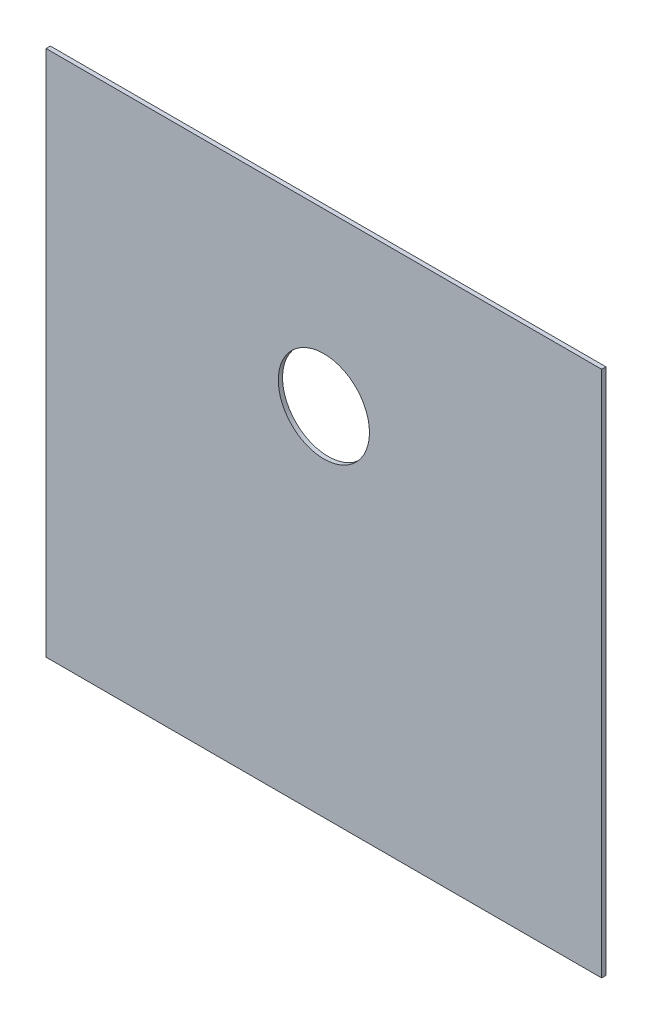
SolidWorks part; units mm, degrees
ref_plane "Front Plane" through (0, 0, 0) normal (0, 0, 1) x (1, 0, 0)
ref_plane "Top Plane" through (0, 0, 0) normal (0, 1, 0) x (1, 0, 0)
ref_plane "Right Plane" through (0, 0, 0) normal (1, 0, 0) x (0, 0, -1)
sketch "Sketch1" plane through (0, 0, 0) normal (0, 0, 1) x (1, 0, 0)
  line L1 (195, -185) -> (-195, -185)
  line L2 (195, -185) -> (195, 185)
  line L3 (195, 185) -> (-195, 185)
  line L4 (-195, -185) -> (-195, 185)
  line L5 (195, -185) -> (-195, 185) construction
  line L6 (195, 185) -> (-195, -185) construction
  point P0 (0, 0)
extrude "Boss-Extrude1" add sketch "Sketch1" along normal blind 3
sketch "Sketch2" plane through (0, 0, 3) normal (0, 0, 1) x (1, 0, 0)
  circle A0 centre (0, 65) radius 32
extrude "Cut-Extrude1" cut sketch "Sketch2" against normal through all
